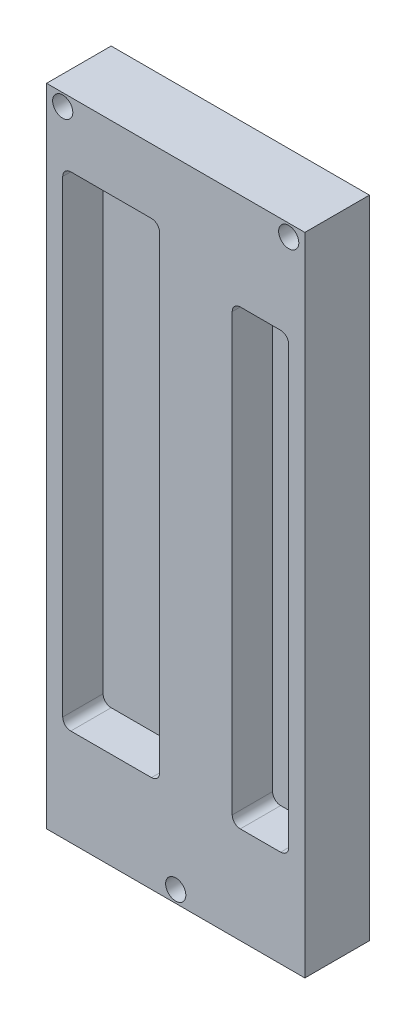
SolidWorks part; units mm, degrees
ref_plane "Plan de face" through (0, 0, 0) normal (0, 0, 1) x (1, 0, 0)
ref_plane "Plan de dessus" through (0, 0, 0) normal (0, 1, 0) x (1, 0, 0)
ref_plane "Plan de droite" through (0, 0, 0) normal (1, 0, 0) x (0, 0, -1)
sketch "Esquisse1" plane through (0, 0, 0) normal (0, 0, 1) x (1, 0, 0)
  line L1 (0, 0) -> (32, 0)
  line L2 (0, 0) -> (0, 80)
  line L3 (0, 80) -> (32, 80)
  line L4 (32, 0) -> (32, 80)
  circle A4 centre (2, 78.5) radius 1.25
  circle A5 centre (30, 78.5) radius 1.25
  circle A6 centre (16, 1.5) radius 1.25
  point P0 (32, 0.2859)
  point P1 (32, 80)
  point P2 (0, 0)
  point P7 (0, 0)
  point P10 (32, 0)
  point P14 (31.8983, 80)
  point P15 (0, 80)
  point P22 (0, 80)
  point P23 (0.1003, 80)
  dimension "D4" = 2
  dimension "D1" = 80
  dimension "D2" = 32
  dimension "D5" = 2
  dimension "D6" = 1.5
  dimension "D7" = 1.5
  dimension "D8" = 16
  dimension "D9" = 1.5
extrude "Boss.-Extru.2" add sketch "Esquisse1" along normal blind 8
sketch "Esquisse2" plane through (0, 0, 8) normal (0, 0, 1) x (1, 0, 0)
  line L0 (0, 80) -> (0, 0) construction
  line L1 (24, 68) -> (29, 68)
  line L2 (23, 67) -> (23, 13)
  line L3 (24, 12) -> (29, 12)
  line L4 (30, 67) -> (30, 13)
  line L5 (3, 72) -> (13, 72)
  line L6 (2, 71) -> (2, 13)
  line L7 (3, 12) -> (13, 12)
  line L8 (14, 71) -> (14, 13)
  line L9 (32, 80) -> (0, 80) construction
  arc A0 (2, 13) -> (3, 12) centre (3, 13) ccw
  arc A1 (13, 12) -> (14, 13) centre (13, 13) ccw
  arc A2 (23, 13) -> (24, 12) centre (24, 13) ccw
  arc A3 (29, 12) -> (30, 13) centre (29, 13) ccw
  arc A4 (29, 68) -> (30, 67) centre (29, 67) cw
  arc A5 (24, 68) -> (23, 67) centre (24, 67) ccw
  arc A6 (13, 72) -> (14, 71) centre (13, 71) cw
  arc A7 (3, 72) -> (2, 71) centre (3, 71) ccw
  point P24 (8, 12)
  point P25 (26.5, 12)
  dimension "D1" = 1
  dimension "D2" = 60
  dimension "D3" = 56
  dimension "D4" = 12
  dimension "D5" = 2
  dimension "D6" = 9
  dimension "D7" = 7
  dimension "D8" = 12
  dimension "D9" = 8
extrude "Enlèv. mat.-Extru.1" cut sketch "Esquisse2" against normal blind 5
